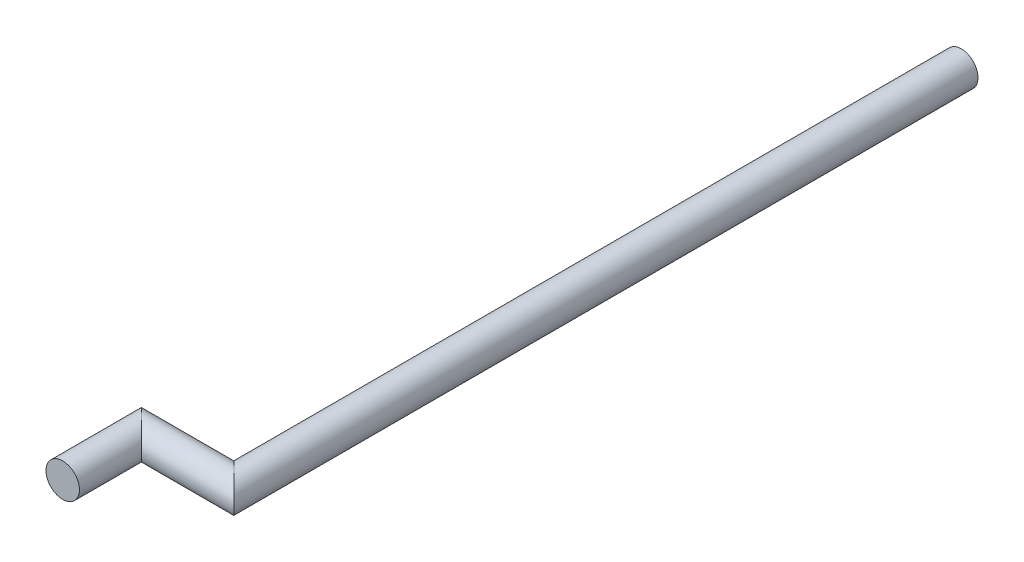
SolidWorks part; units mm, degrees
material "Plain Carbon Steel"
ref_plane "Front Plane" through (0, 0, 0) normal (0, 0, 1) x (1, 0, 0)
ref_plane "Top Plane" through (0, 0, 0) normal (0, 1, 0) x (1, 0, 0)
ref_plane "Right Plane" through (0, 0, 0) normal (1, 0, 0) x (0, 0, -1)
sketch "Sketch1" plane through (0, 0, 0) normal (0, 0, 1) x (1, 0, 0)
  circle A0 centre (0, 0) radius 0.85
  dimension "D1" = 1.7
sketch "Sketch2" plane through (0, 0, 0) normal (0, 1, 0) x (1, 0, 0)
  line L0 (0, 0) -> (0, 4)
  line L1 (0, 4) -> (4.7, 4)
  line L2 (4.7, 4) -> (4.7, 41)
  dimension "D1" = 4
  dimension "D2" = 4.7
  dimension "D3" = 37
sweep "Sweep1" add profiles "Sketch1" path "Sketch2"
